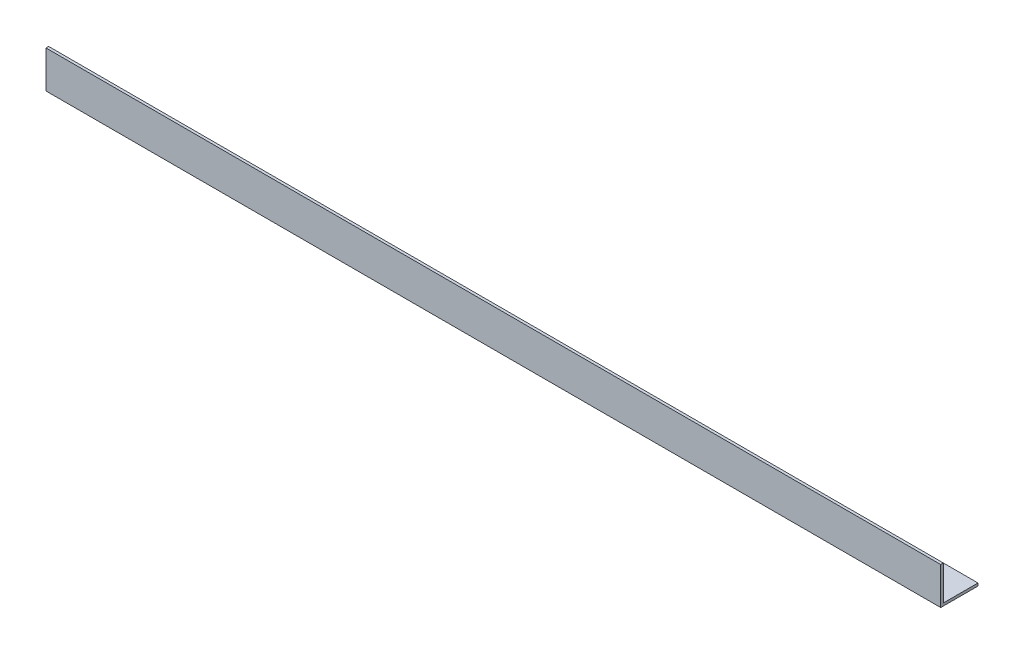
SolidWorks part; units mm, degrees
material "6061 Alloy"
ref_plane "Front Plane" through (0, 0, 0) normal (0, 0, 1) x (1, 0, 0)
ref_plane "Top Plane" through (0, 0, 0) normal (0, 1, 0) x (1, 0, 0)
ref_plane "Right Plane" through (0, 0, 0) normal (1, 0, 0) x (0, 0, -1)
sketch "Sketch1" plane through (0, 0, 0) normal (1, 0, 0) x (0, 0, -1)
  line L0 (0, 0) -> (0, 44.45)
  line L1 (0, 44.45) -> (3.175, 44.45)
  line L2 (3.175, 44.45) -> (3.175, 3.175)
  line L3 (3.175, 3.175) -> (44.45, 3.175)
  line L4 (44.45, 3.175) -> (44.45, 0)
  line L5 (44.45, 0) -> (0, 0)
  dimension "D1" = 44.45
  dimension "D2" = 44.45
  dimension "D3" = 3.175
  dimension "D4" = 3.175
extrude "Boss-Extrude1" add sketch "Sketch1" along normal blind 1066.8
sketch "Sketch2" plane through (0, 3.175, 0) normal (0, 1, 0) x (1, 0, 0)
  line L0 (1066.8, 0) -> (0, 0) construction
  line L1 (0, 44.45) -> (0, 3.175) construction
  line L2 (533.4, 44.45) -> (533.4, 0) construction
  line L3 (1066.8, 44.45) -> (0, 44.45) construction
  circle A0 centre (120.65, 22.225) radius 2.4574
  circle A1 centre (395.8158, 22.225) radius 2.4575
  circle A3 centre (670.9842, 22.225) radius 2.4575
  circle A4 centre (946.15, 22.225) radius 2.4574
  dimension "D3" = 4.9149
  dimension "D5" = 275.1658
  dimension "D1" = 22.225
  dimension "D2" = 120.65
  dimension "D4" = 2
extrude "Cut-Extrude1" cut sketch "Sketch2" against normal blind 889
